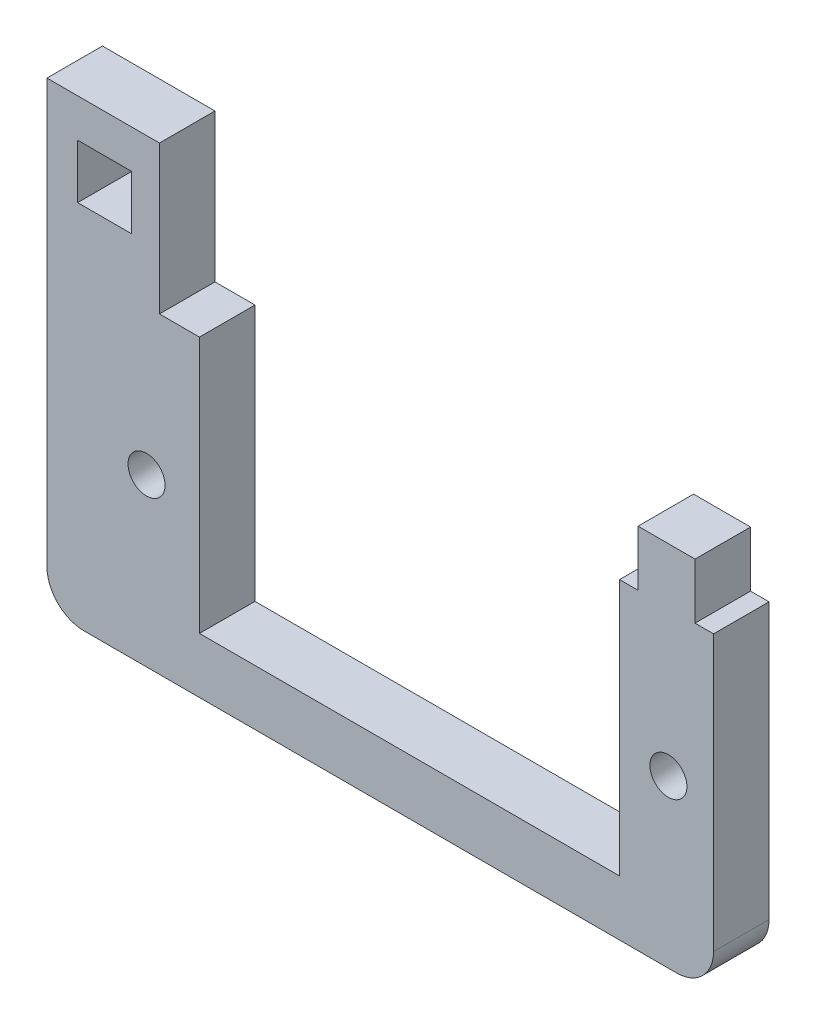
SolidWorks part; units mm, degrees
ref_plane "Front Plane" through (0, 0, 0) normal (0, 0, 1) x (1, 0, 0)
ref_plane "Top Plane" through (0, 0, 0) normal (0, 1, 0) x (1, 0, 0)
ref_plane "Right Plane" through (0, 0, 0) normal (1, 0, 0) x (0, 0, -1)
sketch "Sketch1" plane through (0, 0, 0) normal (0, 0, 1) x (1, 0, 0)
  line L0 (28.1854, -11.5186) -> (-7.8368, -11.5186)
  line L1 (-7.8368, 13.3514) -> (-1.7568, 13.3514)
  line L2 (-1.7568, 13.3514) -> (-1.7568, 5.3514)
  line L3 (-1.7568, 5.3514) -> (0.4054, 5.3514)
  line L4 (0.4054, 5.3514) -> (0.4054, -8.5186)
  line L5 (0.4054, -8.5186) -> (23.1054, -8.5186)
  line L6 (23.1054, -8.5186) -> (23.1054, 5.3514)
  line L7 (23.1054, 5.3514) -> (24.1054, 5.3514)
  line L8 (24.1054, 5.3514) -> (24.1054, 8.3514)
  line L9 (24.1054, 8.3514) -> (27.1854, 8.3514)
  line L10 (27.1854, 8.3514) -> (27.1854, 5.3514)
  line L11 (27.1854, 5.3514) -> (28.1854, 5.3514)
  line L12 (28.1854, 5.3514) -> (28.1854, -11.5186)
  line L13 (-7.8368, -11.5186) -> (-7.8368, 13.3514)
  line L15 (-6.1768, 11.2714) -> (-3.2568, 11.2714)
  line L16 (-6.1768, 11.2714) -> (-6.1768, 8.3514)
  line L17 (-6.1768, 8.3514) -> (-3.2568, 8.3514)
  line L18 (-3.2568, 11.2714) -> (-3.2568, 8.3514)
  circle A0 centre (-2.4546, -2.5186) radius 1
  circle A1 centre (25.7454, -2.5186) radius 1
  dimension "D6" = 2
  dimension "D13" = 2
  dimension "D14" = 7.87
  dimension "D15" = 7.87
  dimension "D20" = 2.86
  dimension "D21" = 25.34
  dimension "D24" = 1.44
  dimension "D25" = 5.3822
  dimension "D1" = 8
  dimension "D2" = 6.08
  dimension "D3" = 22.7
  dimension "D4" = 13.87
  dimension "D5" = 13.87
  dimension "D7" = 1
  dimension "D8" = 3.08
  dimension "D9" = 3
  dimension "D10" = 3
  dimension "D11" = 1
  dimension "D12" = 16.87
  dimension "D16" = 2.92
  dimension "D17" = 2.92
  dimension "D18" = 3
  dimension "D19" = 1.5
  dimension "D22" = 25.8622
  dimension "D23" = 5.3822
extrude "Boss-Extrude1" add sketch "Sketch1" along normal blind 3
fillet "Fillet1" radius 2 2 edges at (-7.8368, -11.5186, 1.5) (28.1854, -11.5186, 1.5)
